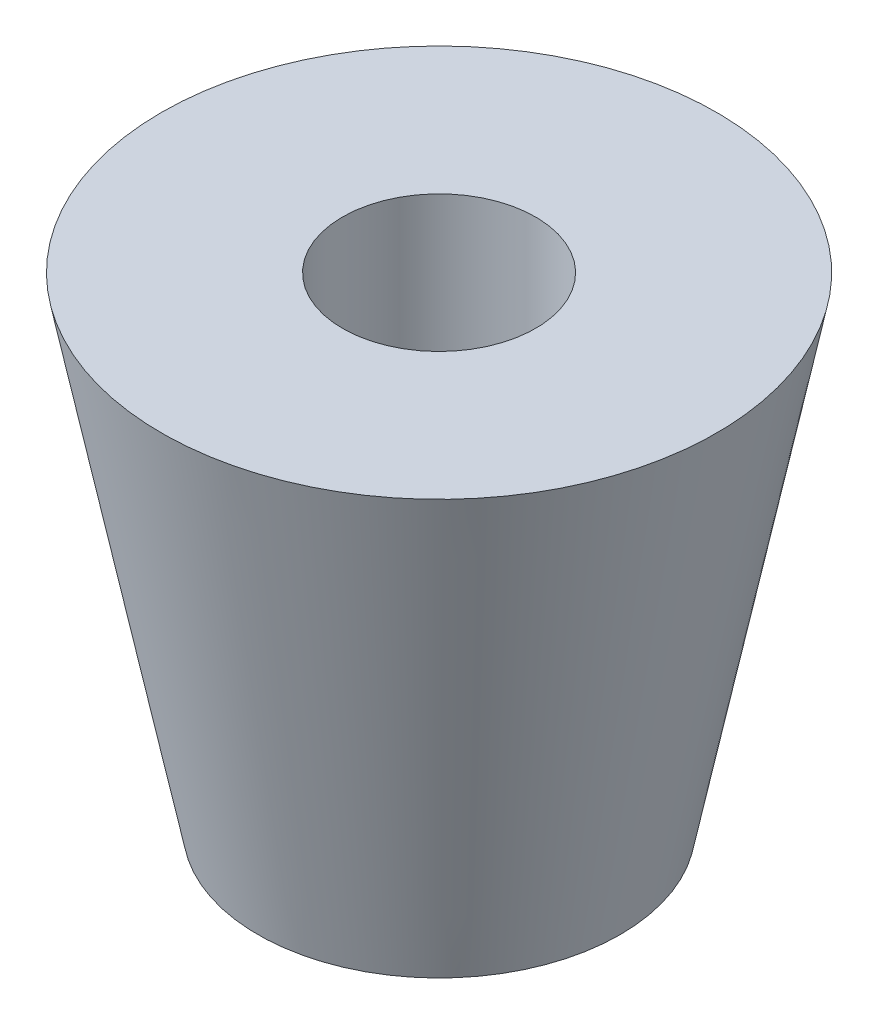
SolidWorks part; units mm, degrees
ref_plane "Plan de face" through (0, 0, 0) normal (0, 0, 1) x (1, 0, 0)
ref_plane "Plan de dessus" through (0, 0, 0) normal (0, 1, 0) x (1, 0, 0)
ref_plane "Plan de droite" through (0, 0, 0) normal (1, 0, 0) x (0, 0, -1)
sketch "Esquisse2" plane through (0, 0, 0) normal (0, 0, 1) x (1, 0, 0)
  line L0 (0, 33.6102) -> (0, -33.6102) construction
  point P2 (0, 0)
sketch "Esquisse1" plane through (0, 0, 0) normal (0, 0, 1) x (1, 0, 0)
  line L0 (0, 0) -> (11.5, 0)
  line L1 (11.5, 0) -> (7.5, -20)
  line L2 (7.5, -20) -> (0, -20)
  line L3 (0, -20) -> (0, 0)
  dimension "D1" = 7.5
  dimension "D2" = 11.5
  dimension "D3" = 20
revolve "Révolution1" add sketch "Esquisse1" angle 360 about L0
sketch "Esquisse3" plane through (0, 0, 0) normal (0, 1, 0) x (1, 0, 0)
  circle A0 centre (0, 0) radius 4
  dimension "D1" = 8
extrude "Enlèv. mat.-Extru.1" cut sketch "Esquisse3" against normal through all
